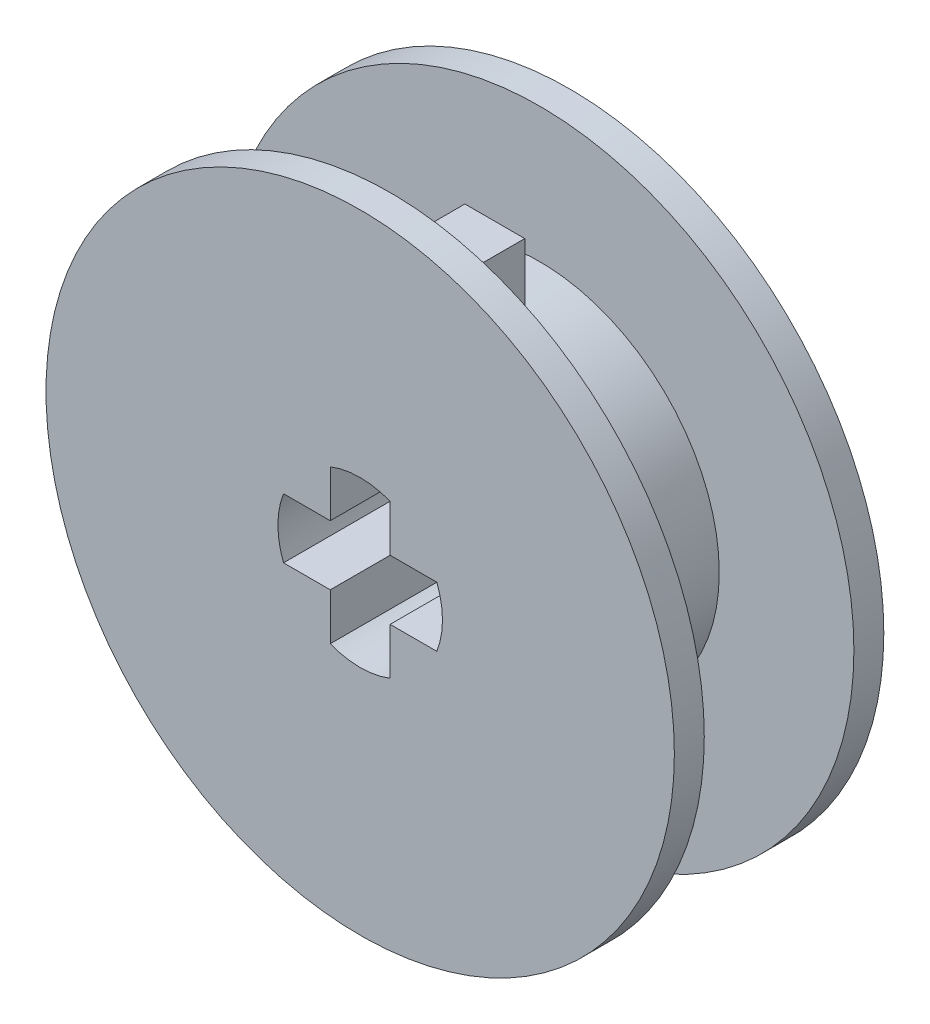
SolidWorks part; units mm, degrees
ref_plane "Plan de face" through (0, 0, 0) normal (0, 0, 1) x (1, 0, 0)
ref_plane "Plan de dessus" through (0, 0, 0) normal (0, 1, 0) x (1, 0, 0)
ref_plane "Plan de droite" through (0, 0, 0) normal (1, 0, 0) x (0, 0, -1)
sketch "Esquisse1" plane through (0, 0, 0) normal (0, 0, 1) x (1, 0, 0)
  line L0 (-2.75, 0) -> (2.75, 0) construction
  line L1 (-2.5617, 1) -> (-1, 1)
  line L2 (-1, -1) -> (-1, -2.5617)
  line L3 (-2.5617, -1) -> (-1, -1)
  line L4 (1, 1) -> (2.5617, 1)
  line L5 (1, -1) -> (1, -2.5617)
  line L6 (-1, 2.5617) -> (-1, 1)
  line L7 (1, -1) -> (2.5617, -1)
  line L8 (1, 2.5617) -> (1, 1)
  line L9 (0, 2.75) -> (0, -2.75) construction
  circle A0 centre (0, 0) radius 6
  arc A1 (-2.5617, 1) -> (-2.5617, -1) centre (0, 0) ccw
  arc A2 (1, 2.5617) -> (-1, 2.5617) centre (0, 0) ccw
  arc A3 (2.5617, -1) -> (2.5617, 1) centre (0, 0) ccw
  arc A4 (-1, -2.5617) -> (1, -2.5617) centre (0, 0) ccw
  point P1 (-1, 1.7809)
  dimension "D2" = 5.5
  dimension "D1" = 12
  dimension "D3" = 2
  dimension "D4" = 2
extrude "Boss.-Extru.1" add sketch "Esquisse1" along normal blind 2.5
sketch "Esquisse2" plane through (0, 0, 2.5) normal (0, 0, 1) x (1, 0, 0)
  line L0 (-1, 2.5617) -> (-1, 1)
  line L1 (-1, 1) -> (-2.5617, 1)
  line L2 (1, 1) -> (1, 2.5617)
  line L4 (2.5617, 1) -> (1, 1)
  line L5 (1, -1) -> (2.5617, -1)
  line L6 (1, -2.5617) -> (1, -1)
  line L7 (-1, -1) -> (-1, -2.5617)
  line L8 (-2.5617, -1) -> (-1, -1)
  circle A0 centre (0, 0) radius 10.5
  arc A1 (1, 2.5617) -> (-1, 2.5617) centre (0, 0) ccw
  arc A2 (2.5617, -1) -> (2.5617, 1) centre (0, 0) ccw
  arc A3 (-1, -2.5617) -> (1, -2.5617) centre (0, 0) ccw
  arc A4 (-2.5617, 1) -> (-2.5617, -1) centre (0, 0) ccw
  point P26 (0, 0)
  point P28 (0, 0)
  dimension "D1" = 21
  dimension "D2" = 4
extrude "Boss.-Extru.4" add sketch "Esquisse2" along normal blind 1
sketch "Esquisse3" plane through (0, 0, 0) normal (0, 0, -1) x (-1, 0, 0)
  line L0 (-1, 1) -> (-1, 2.5617) construction
  line L1 (-1, 5.9161) -> (1, 5.9161)
  line L2 (-1, 5.9161) -> (-1, 7.9161)
  line L3 (-1, 7.9161) -> (1, 7.9161)
  line L4 (1, 5.9161) -> (1, 7.9161)
  line L5 (1, 2.5617) -> (1, 1) construction
  circle A0 centre (0, 0) radius 6 construction
  point P8 (0, 0)
  dimension "D1" = 2
extrude "Boss.-Extru.5" add sketch "Esquisse3" against normal blind 1
mirror "Symétrie1" of "Boss.-Extru.4", "Boss.-Extru.1", "Boss.-Extru.5"
